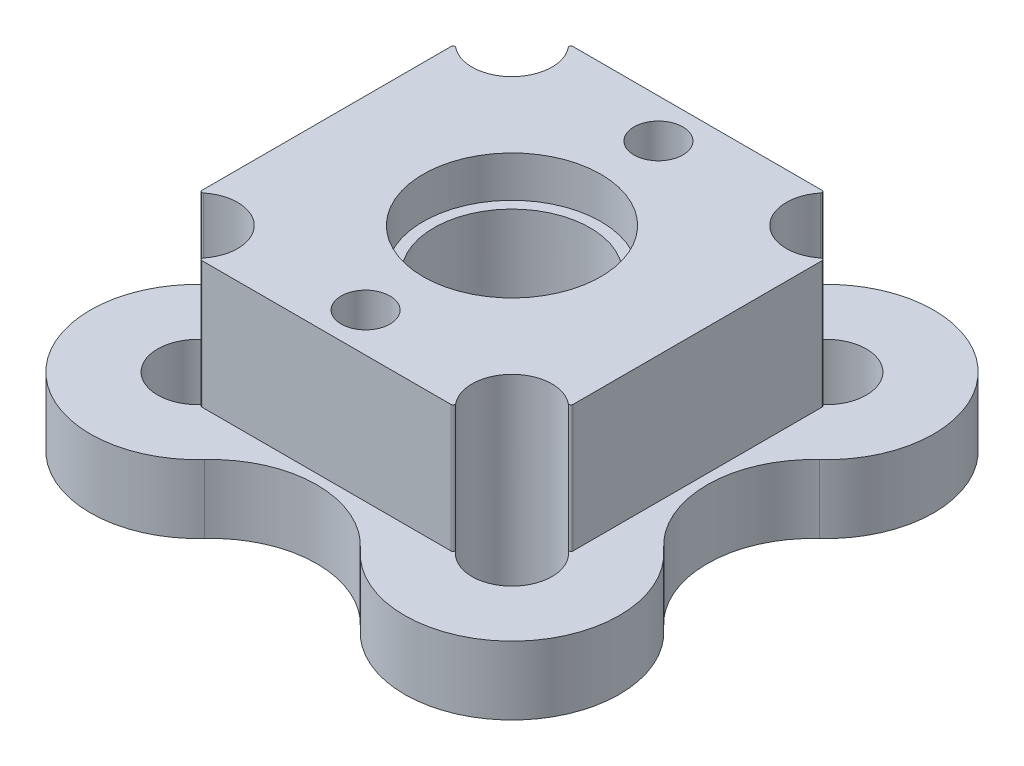
SolidWorks part; units mm, degrees
material "POM Acetal Copolymer"
ref_plane "Front Plane" through (0, 0, 0) normal (0, 0, 1) x (1, 0, 0)
ref_plane "Top Plane" through (0, 0, 0) normal (0, 1, 0) x (1, 0, 0)
ref_plane "Right Plane" through (0, 0, 0) normal (1, 0, 0) x (0, 0, -1)
sketch "Sketch1" plane through (0, 0, 0) normal (0, 1, 0) x (1, 0, 0)
  line L0 (-8.05, 8.05) -> (8.05, 8.05) construction
  line L1 (-994.8872, -10) -> (49005.1128, -10) construction
  line L2 (8.05, -8.05) -> (8.05, -6) construction
  line L3 (-994.8167, 10) -> (49005.1833, 10) construction
  line L4 (8.05, -8.05) -> (8.05, 8.05) construction
  line L5 (8.05, 8.05) -> (8.05, 0) construction
  line L6 (8.05, -8.05) -> (-8.05, -8.05) construction
  line L7 (0, 0) -> (8.05, 8.05) construction
  line L9 (0, 0) -> (8.05, -8.05) construction
  line L10 (-8.05, 8.05) -> (0, 0) construction
  line L11 (-8.05, -8.05) -> (0, 0) construction
  line L13 (0, -1000) -> (0, 49000) construction
  line L14 (-1000, 0) -> (49000, 0) construction
  line L15 (8.05, -6) -> (8.05, -8.05) construction
  line L16 (-8.05, 8.05) -> (-8.05, -8.05) construction
  line L17 (10, -1000) -> (10, 49000) construction
  line L18 (-10, -1000) -> (-10, 49000) construction
  line L19 (3.5199, 1.9) -> (3.5199, -1.9) construction
  line L20 (-3.5199, 1.9) -> (-3.5199, -1.9) construction
  line L21 (-1002.9205, 1.9) -> (48997.0795, 1.9) construction
  line L28 (-3.5199, -1.9) -> (3.5199, -1.9) construction
  line L30 (0, -3.9) -> (3.3775, -1.95) construction
  line L32 (3.3775, -1.95) -> (3.3775, 1.95) construction
  line L34 (3.3775, 1.95) -> (0, 3.9) construction
  line L35 (0, 3.9) -> (-3.3775, 1.95) construction
  line L36 (-3.3775, 1.95) -> (-3.3775, -1.95) construction
  line L37 (-3.3775, -1.95) -> (0, -3.9) construction
  circle A0 centre (-8.05, 8.05) radius 2.05 construction
  circle A1 centre (-8.05, -8.05) radius 2.05 construction
  circle A2 centre (8.05, -8.05) radius 2.05 construction
  circle A3 centre (8.05, 8.05) radius 2.05 construction
  circle A4 centre (0, 0) radius 1.6 construction
  circle A5 centre (0, -7.5) radius 1.25
  circle A6 centre (0, 7.5) radius 1.25
  arc A7 (3.9889, -11.7591) -> (11.7591, -3.9889) centre (8.05, -8.05) ccw
  arc A8 (-11.7591, 3.9889) -> (-3.9889, 11.7591) centre (-8.05, 8.05) cw
  arc A9 (11.7591, 3.9889) -> (11.7591, -3.9889) centre (15.4021, 0) ccw
  arc A10 (11.7591, 3.9889) -> (3.9889, 11.7591) centre (8.05, 8.05) ccw
  arc A11 (-11.7591, 3.9889) -> (-11.7591, -3.9889) centre (-15.4021, 0) cw
  arc A13 (3.9889, 11.7591) -> (-3.9889, 11.7591) centre (0, 15.4021) cw
  circle A14 centre (8.05, -8.05) radius 2.05 construction
  arc A15 (3.9889, -11.7591) -> (-3.9889, -11.7591) centre (0, -15.4021) ccw
  circle A16 centre (8.05, 8.05) radius 2.05 construction
  arc A18 (-3.9889, -11.7591) -> (-11.7591, -3.9889) centre (-8.05, -8.05) cw
  arc A19 (-3.5199, 1.9) -> (3.5199, 1.9) centre (0, 0) cw construction
  circle A25 centre (0, 0) radius 3.3775 construction
  arc A26 (-3.5199, -1.9) -> (3.5199, -1.9) centre (0, 0) ccw construction
  point P46 (0, 0)
  dimension "D1" = 4.1
  dimension "D7" = 3.2
  dimension "D8" = 2.5
  dimension "D9" = 20
  dimension "D11" = 4
  dimension "D14" = 5.5
  dimension "D13" = 5.5
  dimension "D10" = 20
  dimension "D4" = 16.1
  dimension "D2" = 16.1
  dimension "D6" = 15
  dimension "D15" = 7.8
  dimension "D22" = 3.8
extrude "Boss-Extrude1" add sketch "Sketch1" along normal blind 3.5
sketch "Sketch3" plane through (0, 3.5, 0) normal (0, 1, 0) x (1, 0, 0)
  circle A2 centre (-8.05, -8.05) radius 2.05 construction
  circle A3 centre (-8.05, 8.05) radius 2.05 construction
  circle A4 centre (8.05, 8.05) radius 2.05 construction
  circle A5 centre (8.05, -8.05) radius 2.05 construction
  circle A7 centre (-8.05, 8.05) radius 2.05
  circle A8 centre (8.05, 8.05) radius 2.05
  circle A9 centre (8.05, -8.05) radius 2.05
  circle A10 centre (-8.05, -8.05) radius 2.05
extrude "Cut-Extrude3" cut sketch "Sketch3" against normal through all
sketch "Sketch6" plane through (0, 3.5, 0) normal (0, 1, 0) x (1, 0, 0)
  line L0 (-1000, 0) -> (49000, 0) construction
  line L1 (0, -1000) -> (0, 49000) construction
  line L2 (6.6009, 9.5) -> (-6.6009, 9.5)
  line L3 (-9.5, -6.6009) -> (-9.5, 6.6009)
  line L4 (-6.6009, -9.5) -> (6.6009, -9.5)
  line L5 (9.5, -6.6009) -> (9.5, 6.6009)
  line L6 (0, -201000) -> (0, 249000) construction
  line L7 (-201000, 0) -> (249000, 0) construction
  line L11 (-10, -1000) -> (-10, 49000) construction
  line L12 (-1000, -10) -> (49000, -10) construction
  line L13 (-1000, 10) -> (49000, 10) construction
  line L14 (10, -1000) -> (10, 49000) construction
  arc A0 (9.5, -6.6009) -> (6.6009, -9.5) centre (8.05, -8.05) ccw
  arc A2 (6.6009, 9.5) -> (9.5, 6.6009) centre (8.05, 8.05) ccw
  arc A3 (-9.5, 6.6009) -> (-6.6009, 9.5) centre (-8.05, 8.05) ccw
  circle A7 centre (8.05, -8.05) radius 2.05 construction
  arc A8 (-6.6009, -9.5) -> (-9.5, -6.6009) centre (-8.05, -8.05) ccw
  circle A9 centre (-8.05, -8.05) radius 2.05 construction
  circle A11 centre (8.05, 8.05) radius 2.05 construction
  circle A12 centre (8.05, -8.05) radius 2.05 construction
  circle A13 centre (-8.05, -8.05) radius 2.05 construction
  circle A14 centre (-8.05, 8.05) radius 2.05 construction
  circle A15 centre (0, -7.5) radius 1.25
  circle A16 centre (0, 7.5) radius 1.25
  circle A17 centre (0, 0) radius 1.6 construction
  circle A18 centre (0, 0) radius 1.6 construction
  circle A19 centre (0, -7.5) radius 1.25 construction
  circle A20 centre (0, 7.5) radius 1.25 construction
  dimension "D1" = 19
  dimension "D2" = 19
  dimension "D7" = 20
  dimension "D9" = 20
extrude "Boss-Extrude2" add sketch "Sketch6" along normal blind 6.5
sketch "Sketch10" plane through (0, 10, 0) normal (0, 1, 0) x (1, 0, 0)
  line L0 (-3.5199, 1.9) -> (-3.5199, -1.9)
  line L1 (-3.5199, 1.9) -> (-3.5199, -1.9) construction
  line L2 (3.5199, 1.9) -> (3.5199, -1.9)
  line L3 (3.5199, 1.9) -> (3.5199, -1.9) construction
  arc A0 (-3.5199, 1.9) -> (3.5199, 1.9) centre (0, 0) cw
  arc A1 (-3.5199, -1.9) -> (3.5199, -1.9) centre (0, 0) ccw
  arc A2 (-3.5199, -1.9) -> (3.5199, -1.9) centre (0, 0) ccw construction
  arc A3 (3.5199, 1.9) -> (-3.5199, 1.9) centre (0, 0) ccw construction
extrude "Cut-Extrude8" cut sketch "Sketch10" against normal through all
sketch "Sketch9" plane through (0, 10, 0) normal (0, 1, 0) x (1, 0, 0)
  circle A0 centre (0, 0) radius 4
  dimension "D1" = 8
extrude "Cut-Extrude7" cut sketch "Sketch9" against normal through all and the other way through all
sketch "Sketch11" plane through (0, 10, 0) normal (0, 1, 0) x (1, 0, 0)
  circle A0 centre (0, 0) radius 4.55
  dimension "D1" = 9.1
extrude "Cut-Extrude9" cut sketch "Sketch11" against normal blind 2.1
fillet "Fillet5" radius 0.1 8 edges
